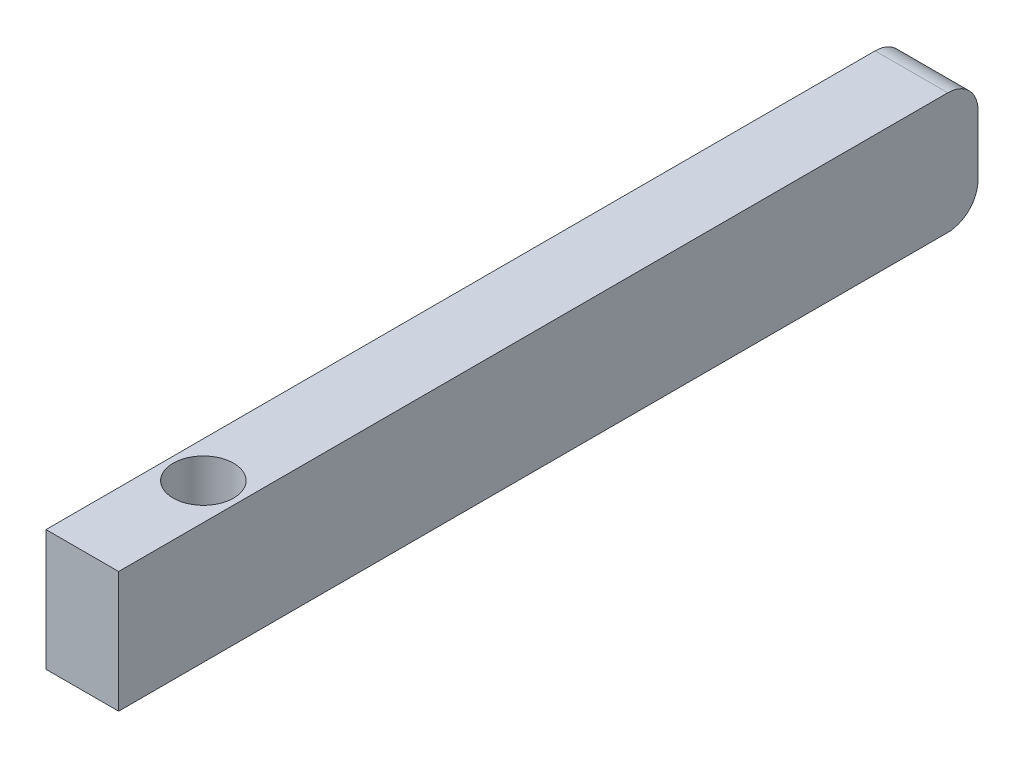
SolidWorks part; units mm, degrees
ref_plane "前视基准面" through (0, 0, 0) normal (0, 0, 1) x (1, 0, 0)
ref_plane "上视基准面" through (0, 0, 0) normal (0, 1, 0) x (1, 0, 0)
ref_plane "右视基准面" through (0, 0, 0) normal (1, 0, 0) x (0, 0, -1)
other "Configuration Table"
sketch "草图1" plane through (0, 0, 0) normal (0, 1, 0) x (1, 0, 0)
  line L49 (-0.6, -2) -> (0.6, -2)
  line L50 (-0.6, -2) -> (-0.6, 5)
  line L51 (-0.6, 5) -> (0.6, 5)
  line L52 (0.6, -2) -> (0.6, 5)
  line L53 (-0.6, 5) -> (0.6, 5)
  line L54 (-0.6, 5) -> (-0.6, 12.2)
  line L55 (-0.6, 12.2) -> (0.6, 12.2)
  line L56 (0.6, 5) -> (0.6, 12.2)
  circle A1 centre (0, 0) radius 0.5
  point P6 (0, 0)
  point P7 (0, -2)
  dimension "D12" = 1
  dimension "D2" = 7.2
  dimension "D3" = 5
  dimension "D4" = 1.2
  dimension "D5" = 2
extrude "凸台-拉伸1" add sketch "草图1" along normal blind 2 contours L51 L56 L55 L54 | L49 L52 L51 L50 A1
fillet "圆角1" radius 0.5 2 edges at (0, 2, -12.2) (0, 0, -12.2)
